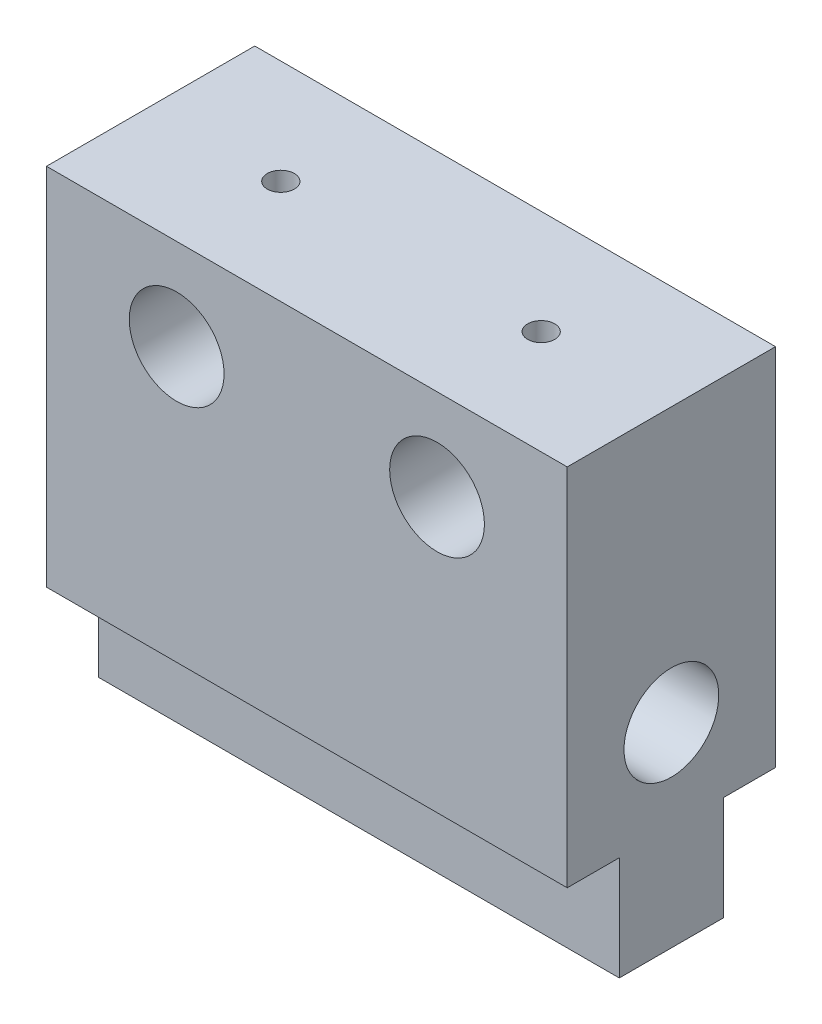
SolidWorks part; units mm, degrees
ref_plane "Front Plane" through (0, 0, 0) normal (0, 0, 1) x (1, 0, 0)
ref_plane "Top Plane" through (0, 0, 0) normal (0, 1, 0) x (1, 0, 0)
ref_plane "Right Plane" through (0, 0, 0) normal (1, 0, 0) x (0, 0, -1)
sketch "Sketch1" plane through (0, 0, 0) normal (0, 0, 1) x (1, 0, 0)
  line L1 (-50, -35) -> (50, -35)
  line L2 (-50, -35) -> (-50, 35)
  line L3 (-50, 35) -> (50, 35)
  line L4 (50, -35) -> (50, 35)
  line L5 (-50, -35) -> (50, 35) construction
  line L6 (-50, 35) -> (50, -35) construction
  point P0 (0, 0)
  dimension "D1" = 70
  dimension "D2" = 100
extrude "Boss-Extrude1" add sketch "Sketch1" along normal mid plane 40
sketch "Sketch2" plane through (0, 0, 20) normal (0, 0, 1) x (1, 0, 0)
  line L0 (0, 0) -> (50, 35) construction
  line L1 (0, 0) -> (-50, 35) construction
  circle A0 centre (25, 17.5) radius 9.1
  circle A1 centre (-25, 17.5) radius 9.1
  dimension "D1" = 18.2
extrude "Cut-Extrude1" cut sketch "Sketch2" against normal through all both and the other way through all
sketch "Sketch3" plane through (-50, 0, 0) normal (-1, 0, 0) x (0, 0, 1)
  line L0 (0, 0) -> (0, -35) construction
  line L1 (20, -35) -> (-20, -35) construction
  circle A0 centre (0, -17.5) radius 9.1
  point P7 (0, -17.5)
  dimension "D1" = 18.2
extrude "Cut-Extrude2" cut sketch "Sketch3" against normal through all both
sketch "Sketch4" plane through (0, 35, 0) normal (0, 1, 0) x (1, 0, 0)
  line L0 (-50, 0) -> (0, 0) construction
  line L1 (-50, -20) -> (-50, 20) construction
  line L3 (0, 0) -> (50, 0) construction
  line L4 (50, -20) -> (50, 20) construction
  circle A0 centre (-25, 0) radius 2.6
  circle A1 centre (25, 0) radius 2.6
  point P5 (-25, 0)
  dimension "D1" = 5.2
extrude "Cut-Extrude4" cut sketch "Sketch4" against normal blind 20
sketch "Sketch5" plane through (0, -35, 0) normal (0, -1, 0) x (1, 0, 0)
  line L0 (50, 20) -> (50, -20) construction
  line L1 (-50, -10) -> (50, -10)
  line L2 (-50, -10) -> (-50, 10)
  line L3 (-50, 10) -> (50, 10)
  line L4 (50, -10) -> (50, 10)
  line L5 (-50, -10) -> (50, 10) construction
  line L6 (-50, 10) -> (50, -10) construction
  point P0 (0, 0)
  dimension "D1" = 20
extrude "Boss-Extrude2" add sketch "Sketch5" along normal blind 20
